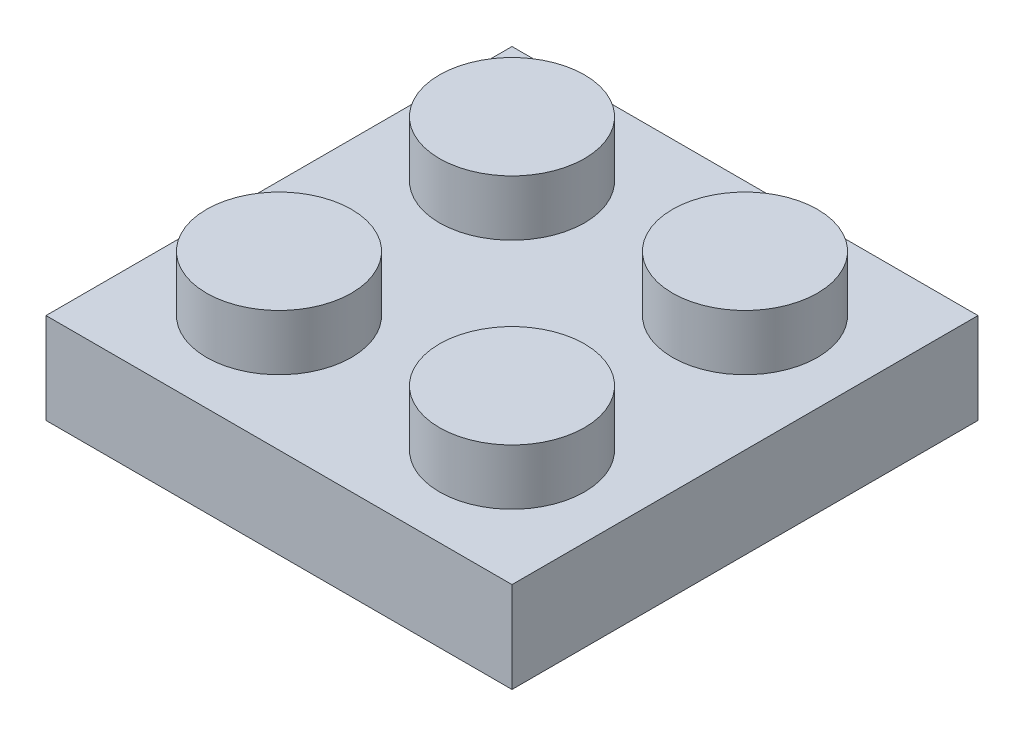
SolidWorks part; units mm, degrees
ref_plane "Front Plane" through (0, 0, 0) normal (0, 0, 1) x (1, 0, 0)
ref_plane "Top Plane" through (0, 0, 0) normal (0, 1, 0) x (1, 0, 0)
ref_plane "Right Plane" through (0, 0, 0) normal (1, 0, 0) x (0, 0, -1)
sketch "Sketch1" plane through (0, 0, 0) normal (0, 1, 0) x (1, 0, 0)
  line L0 (-43.7442, -33.8665) -> (-43.7442, -49.7665)
  line L1 (-43.7442, -49.7665) -> (-27.8442, -49.7665)
  line L2 (-27.8442, -49.7665) -> (-27.8442, -33.8665)
  line L3 (-27.8442, -33.8665) -> (-43.7442, -33.8665)
  dimension "D1" = 15.9
  dimension "D2" = 15.9
extrude "Boss-Extrude1" add sketch "Sketch1" along normal blind 3.1
sketch "Sketch2" plane through (0, 0, 0) normal (0, -1, 0) x (1, 0, 0)
  line L0 (-42.2442, 48.2665) -> (-29.3442, 48.2665)
  line L1 (-29.3442, 48.2665) -> (-29.3442, 35.3665)
  line L2 (-29.3442, 35.3665) -> (-42.2442, 35.3665)
  line L3 (-42.2442, 35.3665) -> (-42.2442, 48.2665)
  line L4 (-43.7442, 49.7665) -> (-27.8442, 49.7665) construction
  line L5 (-43.7442, 33.8665) -> (-43.7442, 49.7665) construction
  line L6 (-27.8442, 33.8665) -> (-43.7442, 33.8665) construction
  line L7 (-27.8442, 49.7665) -> (-27.8442, 33.8665) construction
  dimension "D1" = 1.5
  dimension "D2" = 1.5
  dimension "D3" = 1.5
  dimension "D4" = 1.5
extrude "Cut-Extrude1" cut sketch "Sketch2" against normal blind 1.9
sketch "Sketch3" plane through (0, 3.1, 0) normal (0, 1, 0) x (1, 0, 0)
  line L2 (-27.8442, -33.8665) -> (-43.7442, -33.8665) construction
  line L3 (-43.7442, -33.8665) -> (-43.7442, -49.7665) construction
  line L5 (-43.7442, -49.7665) -> (-27.8442, -49.7665) construction
  line L6 (-27.8442, -49.7665) -> (-27.8442, -33.8665) construction
  circle A0 centre (-39.7692, -37.8415) radius 2.475
  circle A1 centre (-31.8192, -37.8415) radius 2.475
  circle A2 centre (-39.7692, -45.7915) radius 2.475
  circle A3 centre (-31.8192, -45.7915) radius 2.475
  dimension "D1" = 4.95
  dimension "D2" = 4.95
  dimension "D3" = 4.95
  dimension "D4" = 4.95
  dimension "D5" = 3.975
  dimension "D8" = 3.975
  dimension "D6" = 3.975
  dimension "D7" = 3.975
  dimension "D9" = 3.975
  dimension "D10" = 3.975
  dimension "D11" = 3.975
  dimension "D12" = 3.975
extrude "Boss-Extrude2" add sketch "Sketch3" along normal blind 1.9
